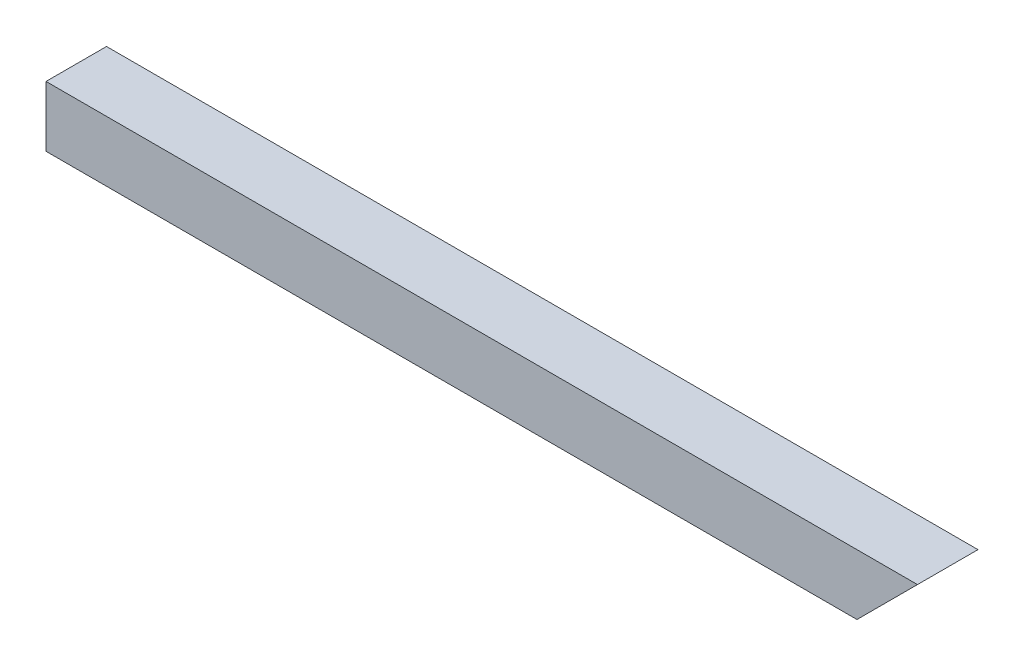
SolidWorks part; units mm, degrees
ref_plane "Front Plane" through (0, 0, 0) normal (0, 0, 1) x (1, 0, 0)
ref_plane "Top Plane" through (0, 0, 0) normal (0, 1, 0) x (1, 0, 0)
ref_plane "Right Plane" through (0, 0, 0) normal (1, 0, 0) x (0, 0, -1)
sketch "Sketch1" plane through (0, 0, 0) normal (1, 0, 0) x (0, 0, -1)
  line L1 (12.5, -12.5) -> (-12.5, -12.5)
  line L2 (12.5, -12.5) -> (12.5, 12.5)
  line L3 (12.5, 12.5) -> (-12.5, 12.5)
  line L4 (-12.5, -12.5) -> (-12.5, 12.5)
  line L5 (12.5, -12.5) -> (-12.5, 12.5) construction
  line L6 (12.5, 12.5) -> (-12.5, -12.5) construction
  line L7 (11.5, -11.5) -> (-11.5, -11.5)
  line L8 (11.5, -11.5) -> (11.5, 11.5)
  line L9 (11.5, 11.5) -> (-11.5, 11.5)
  line L10 (-11.5, -11.5) -> (-11.5, 11.5)
  line L11 (11.5, -11.5) -> (-11.5, 11.5) construction
  line L12 (11.5, 11.5) -> (-11.5, -11.5) construction
  point P0 (0, 0)
  point P6 (0, 0)
  dimension "D1" = 25
  dimension "D2" = 1
extrude "Boss-Extrude1" add sketch "Sketch1" along normal blind 360
sketch "Sketch2" plane through (0, 0, 12.5) normal (0, 0, 1) x (1, 0, 0)
  line L0 (360, 12.5) -> (335, -12.5)
  line L1 (360, -12.5) -> (0, -12.5) construction
  line L2 (335, -12.5) -> (360, -12.5)
  line L3 (360, -12.5) -> (360, 12.5)
  dimension "D1" = 45
extrude "Cut-Extrude3" cut sketch "Sketch2" against normal blind 360
